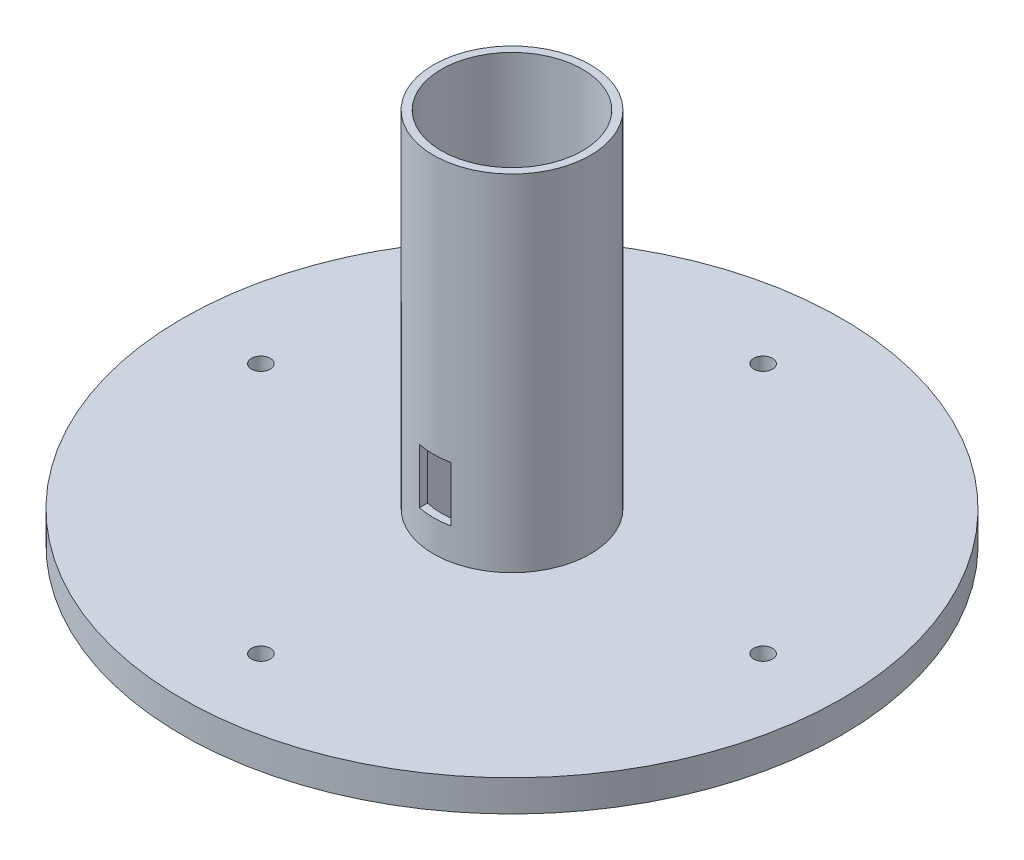
SolidWorks part; units mm, degrees
ref_plane "Front Plane" through (0, 0, 0) normal (0, 0, 1) x (1, 0, 0)
ref_plane "Top Plane" through (0, 0, 0) normal (0, 1, 0) x (1, 0, 0)
ref_plane "Right Plane" through (0, 0, 0) normal (1, 0, 0) x (0, 0, -1)
sketch "Sketch1" plane through (0, 0, 0) normal (0, 0, 1) x (1, 0, 0)
  line L0 (0, 0) -> (0, -114.3) construction
  line L3 (0, -114.3) -> (0, -279.4)
  line L4 (0, -279.4) -> (31.75, -279.4)
  line L5 (31.75, -279.4) -> (31.75, -266.7)
  line L6 (31.75, -266.7) -> (133.35, -266.7)
  line L7 (31.75, -114.3) -> (31.75, -254)
  line L9 (31.75, -254) -> (133.35, -254)
  line L10 (133.35, -254) -> (133.35, -266.7)
  line L11 (31.75, -114.3) -> (0, -114.3)
  dimension "D2" = 114.3
  dimension "D3" = 31.75
  dimension "D4" = 165.1
  dimension "D5" = 12.7
  dimension "D6" = 101.6
  dimension "D7" = 12.7
revolve "Revolve1" add sketch "Sketch1" angle 360 about L0
sketch "Sketch2" plane through (0, -279.4, 0) normal (0, -1, 0) x (1, 0, 0)
  circle A0 centre (0, 0) radius 28.575
extrude "Cut-Extrude2" cut sketch "Sketch2" against normal blind 228.6
ref_plane "Plane1" through (0, 0, 31.75) normal (0, 0, 1) x (1, 0, 0)
sketch "Sketch3" plane through (0, 0, 31.75) normal (0, 0, 1) x (1, 0, 0)
  line L0 (-6.35, -241.3) -> (6.35, -241.3)
  line L2 (133.35, -254) -> (-133.35, -254) construction
  line L4 (0, -219.075) -> (6.35, -219.075)
  line L5 (6.35, -219.075) -> (6.35, -241.3)
  line L8 (-6.35, -241.3) -> (-6.35, -219.075)
  line L9 (-6.35, -219.075) -> (0, -219.075)
  dimension "D1" = 22.225
  dimension "D2" = 6.35
  dimension "D3" = 6.35
  dimension "D4" = 12.7
extrude "Cut-Extrude5" cut sketch "Sketch3" against normal blind 8.89
sketch "Sketch4" plane through (0, -266.7, 0) normal (0, -1, 0) x (1, 0, 0)
  circle A0 centre (0, 101.6) radius 3.81
  circle A1 centre (101.6, 0) radius 3.81
  circle A2 centre (0, 0) radius 101.6 construction
  circle A3 centre (0, -101.6) radius 3.81
  circle A4 centre (-101.6, 0) radius 3.81
  point P14 (0, 0)
  dimension "D1" = 7.62
  dimension "D2" = 203.2
  dimension "D3" = 4
extrude "Cut-Extrude4" cut sketch "Sketch4" against normal blind 12.7
